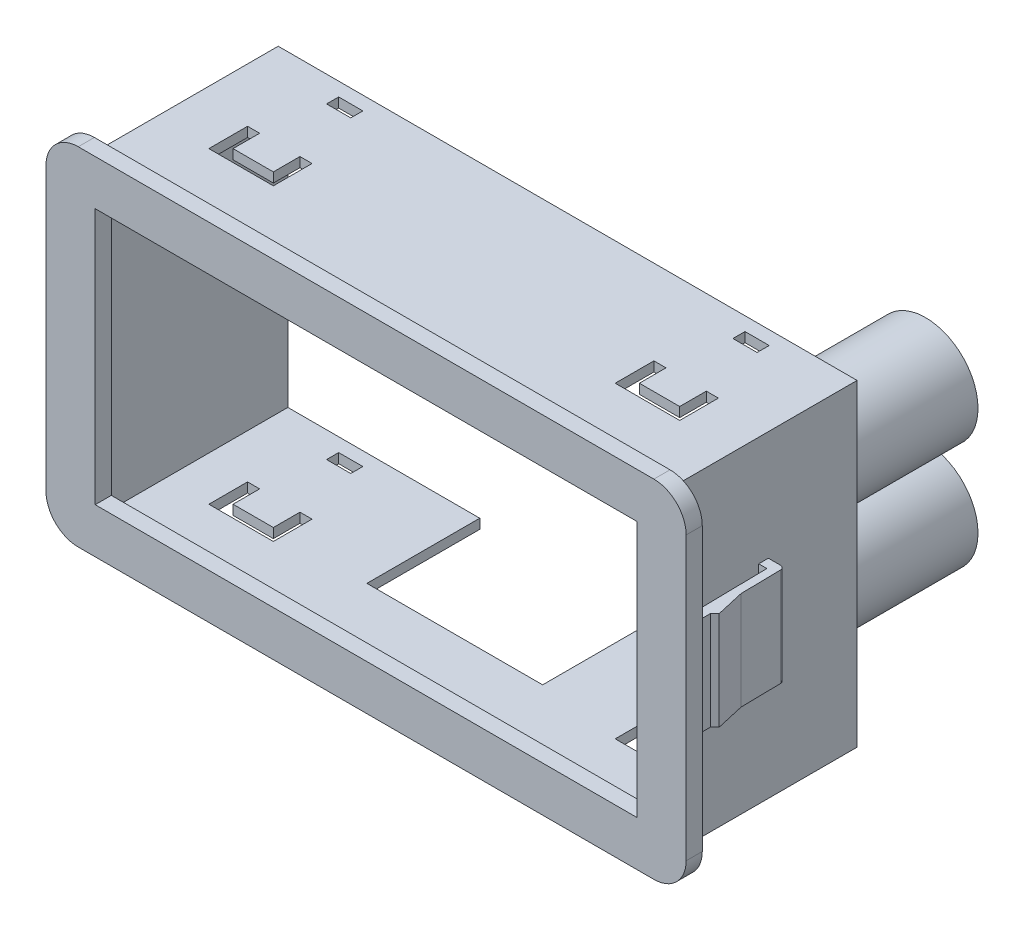
SolidWorks part; units mm, degrees
ref_plane "Спереди" through (0, 0, 0) normal (0, 0, 1) x (1, 0, 0)
ref_plane "Сверху" through (0, 0, 0) normal (0, 1, 0) x (1, 0, 0)
ref_plane "Справа" through (0, 0, 0) normal (1, 0, 0) x (0, 0, -1)
sketch "Эскиз1" plane through (0, 0, 0) normal (0, 0, 1) x (1, 0, 0)
  line L1 (-34.7, 18.5) -> (34.7, 18.5)
  line L2 (-34.7, 18.5) -> (-34.7, -18.5)
  line L3 (-34.7, -18.5) -> (34.7, -18.5)
  line L4 (34.7, 18.5) -> (34.7, -18.5)
  line L5 (-35.9, 19.7) -> (35.9, 19.7)
  line L6 (-35.9, 19.7) -> (-35.9, -19.7)
  line L7 (-35.9, -19.7) -> (35.9, -19.7)
  line L8 (35.9, 19.7) -> (35.9, -19.7)
  point P8 (0, 18.5)
  point P9 (0, 19.7)
  point P11 (-35.9, 0)
  point P12 (-34.7, 0)
  dimension "D1" = 39.4
  dimension "D2" = 1.2
  dimension "D3" = 71.8
  dimension "D4" = 1.2
extrude "Бобышка-Вытянуть1" add sketch "Эскиз1" along normal blind 23
sketch "Эскиз2" plane through (0, 0, 23) normal (0, 0, 1) x (1, 0, 0)
  line L1 (-35.7, 21.5) -> (35.7, 21.5)
  line L2 (-39.7, 17.5) -> (-39.7, -17.5)
  line L3 (-35.7, -21.5) -> (35.7, -21.5)
  line L4 (39.7, 17.5) -> (39.7, -17.5)
  line L5 (-33.6, 15.9) -> (33.6, 15.9)
  line L6 (-33.6, 15.9) -> (-33.6, -15.9)
  line L7 (-33.6, -15.9) -> (33.6, -15.9)
  line L8 (33.6, 15.9) -> (33.6, -15.9)
  arc A0 (35.7, 21.5) -> (39.7, 17.5) centre (35.7, 17.5) cw
  arc A1 (35.7, -21.5) -> (39.7, -17.5) centre (35.7, -17.5) ccw
  arc A2 (-39.7, -17.5) -> (-35.7, -21.5) centre (-35.7, -17.5) ccw
  arc A3 (-35.7, 21.5) -> (-39.7, 17.5) centre (-35.7, 17.5) ccw
  point P6 (-39.7, 0)
  point P9 (-33.6, 0)
  point P10 (0, 21.5)
  point P11 (0, 15.9)
  point P14 (39.7, 0)
  point P15 (0, 0)
  dimension "D5" = 4
  dimension "D1" = 43
  dimension "D2" = 79.4
  dimension "D3" = 31.8
  dimension "D4" = 67.2
extrude "Бобышка-Вытянуть2" add sketch "Эскиз2" along normal blind 2
sketch "Эскиз3" plane through (0, 0, 0) normal (0, 1, 0) x (1, 0, 0)
  line L0 (35.9, -12.2) -> (36.9109, -12.2)
  line L1 (35.9, -23) -> (35.9, 0) construction
  line L2 (36.9109, -12.2) -> (37.1, -22.6)
  line L3 (37.1, -22.6) -> (38.25, -22.6)
  line L4 (38.25, -22.6) -> (38.25, -20.5106)
  line L5 (38.25, -20.5106) -> (38.8, -20)
  line L6 (38.8, -20) -> (38, -16.5)
  line L7 (38, -16.5) -> (37.9089, -11.4909)
  line L8 (37.409, -11) -> (35.9, -11)
  line L9 (35.9, -11) -> (35.9, -12.2)
  line L10 (0, 0) -> (0, -25) construction
  line L11 (35.7, -25) -> (-35.7, -25) construction
  line L12 (35.9, 0) -> (-35.9, 0) construction
  line L13 (39.7, -23) -> (35.7, -23) construction
  arc A0 (37.9089, -11.4909) -> (37.409, -11) centre (37.409, -11.5) ccw
  point P4 (37.7427, -12.7247)
  point P17 (35.9, -19.0685)
  point P19 (35.9, -20.1424)
  point P20 (0, 0)
  point P21 (38, -13.9231)
  point P22 (38.25, -17.655)
  point P27 (0, 0)
  point P28 (36.5225, -22.6)
  point P29 (38.25, -20.3989)
  point P30 (0, 0)
  point P33 (37.9, -11)
  dimension "D12" = 0.5
  dimension "D1" = 2
  dimension "D2" = 77.6
  dimension "D3" = 11
  dimension "D4" = 76.5
  dimension "D5" = 76
  dimension "D6" = 16.5
  dimension "D7" = 20
  dimension "D8" = 0.4
  dimension "D9" = 1.2
  dimension "D10" = 1.2
  dimension "D11" = 120
extrude "Бобышка-Вытянуть3" add sketch "Эскиз3" along normal blind 6.1 and the other way blind 6.1
mirror "Зеркальное отражение1" about plane through (0, 0, 0) normal (1, 0, 0) of "Бобышка-Вытянуть3"
sketch "Эскиз4" plane through (0, -19.7, 0) normal (0, -1, 0) x (1, 0, 0)
  line L0 (-35.9, 0) -> (35.9, 0) construction
  line L1 (-10.9, 0) -> (10.9, 0)
  line L2 (-10.9, 0) -> (-10.9, 14)
  line L3 (-10.9, 14) -> (10.9, 14)
  line L4 (10.9, 0) -> (10.9, 14)
  line L5 (35.9, 23) -> (35.9, 0) construction
  line L6 (-35.7, 25) -> (35.7, 25) construction
  point P6 (0, 14)
  dimension "D1" = 25
  dimension "D2" = 11
extrude "Вырез-Вытянуть1" cut sketch "Эскиз4" against normal up to next
sketch "Эскиз5" plane through (0, 19.7, 0) normal (0, 1, 0) x (1, 0, 0)
  line L0 (-29.2, -10.5) -> (-29.2, -15.3)
  line L1 (-29.2, -15.3) -> (-21.2, -15.3)
  line L2 (-21.2, -15.3) -> (-21.2, -10.5)
  line L3 (-21.2, -10.5) -> (-22.7, -10.5)
  line L4 (-22.7, -10.5) -> (-22.7, -13.8)
  line L5 (-22.7, -13.8) -> (-27.7, -13.8)
  line L6 (-27.7, -13.8) -> (-27.7, -10.5)
  line L7 (-27.7, -10.5) -> (-29.2, -10.5)
  line L8 (-35.9, -23) -> (-35.9, 0) construction
  line L9 (-26.7, -1.7) -> (-23.7, -1.7)
  line L10 (-26.7, -1.7) -> (-26.7, -3.2)
  line L11 (-26.7, -3.2) -> (-23.7, -3.2)
  line L12 (-23.7, -1.7) -> (-23.7, -3.2)
  line L13 (35.9, 0) -> (-35.9, 0) construction
  point P14 (-25.2, -3.2)
  point P15 (-25.2, -13.8)
  dimension "D1" = 1.5
  dimension "D2" = 1.5
  dimension "D3" = 13.2
  dimension "D4" = 5
  dimension "D5" = 10.5
  dimension "D6" = 1.7
  dimension "D7" = 9.2
  dimension "D8" = 13.8
extrude "Вырез-Вытянуть2" cut sketch "Эскиз5" against normal up to next
mirror "Зеркальное отражение2" about plane through (0, 0, 0) normal (1, 0, 0) of "Вырез-Вытянуть2"
mirror "Зеркальное отражение3" about plane through (0, 0, 0) normal (0, 1, 0) of "Зеркальное отражение2", "Вырез-Вытянуть2"
ref_plane "Плоскость1" through (0, 0, 9) normal (0, 0, -1) x (-1, 0, 0)
sketch "Эскиз6" plane through (0, 0, 9) normal (0, 0, -1) x (-1, 0, 0)
  line L1 (35.9, -19.7) -> (-35.9, -19.7) construction
  line L2 (-35.9, 19.7) -> (35.9, 19.7) construction
  line L3 (-35.9, -19.7) -> (-35.9, 19.7) construction
  circle A0 centre (-27.4, 7.2) radius 6.5
  circle A1 centre (-27.4, -6.2) radius 6.5
  point P4 (-27.4, 13.7)
  point P6 (-27.4, -12.7)
  point P10 (-33.9, 7.2)
  point P13 (0, 0)
  dimension "D1" = 13
  dimension "D2" = 7
  dimension "D3" = 6
  dimension "D4" = 2
extrude "Бобышка-Вытянуть4" add sketch "Эскиз6" along normal blind 26 separate body
